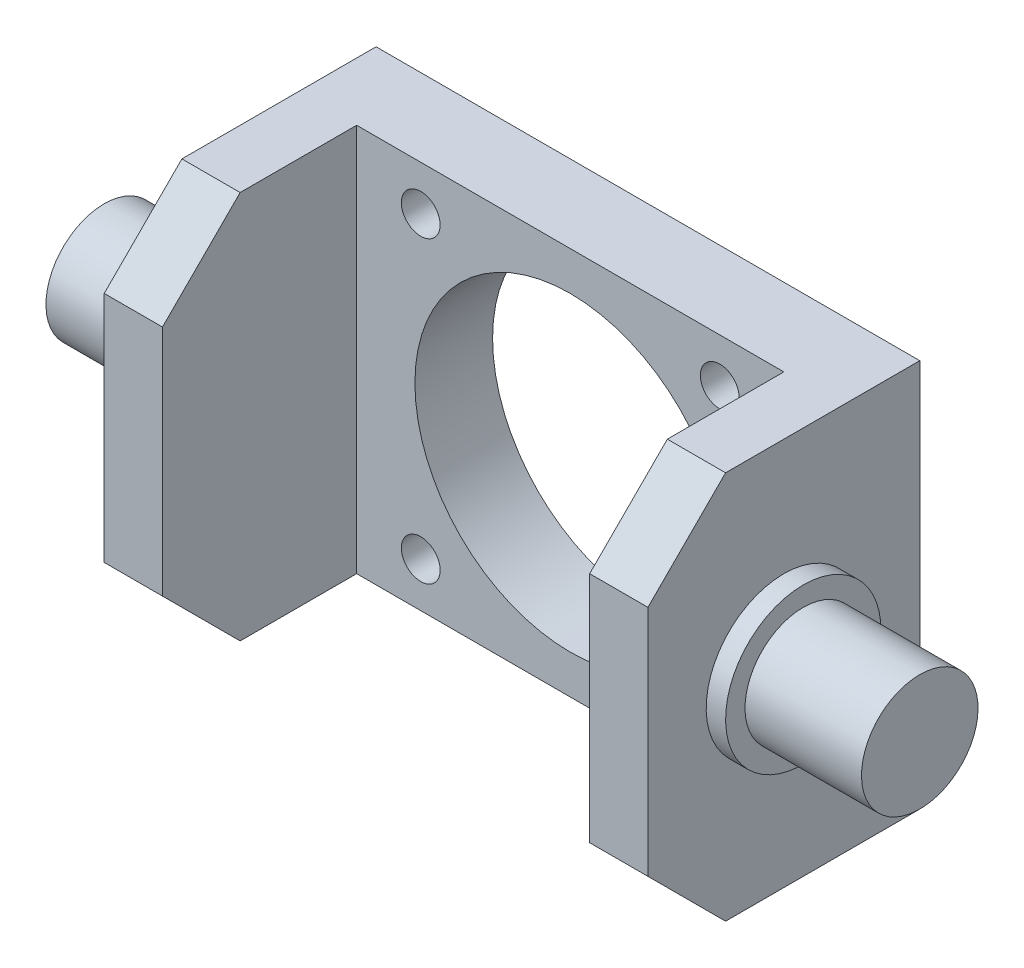
SolidWorks part; units mm, degrees
material "6061 合金"
ref_plane "前视基准面" through (0, 0, 0) normal (0, 0, 1) x (1, 0, 0)
ref_plane "上视基准面" through (0, 0, 0) normal (0, 1, 0) x (1, 0, 0)
ref_plane "右视基准面" through (0, 0, 0) normal (1, 0, 0) x (0, 0, -1)
other "Configuration Table"
sketch "草图1" plane through (0, 0, 0) normal (0, 0, 1) x (1, 0, 0)
  line L1 (-14, 10) -> (14, 10)
  line L2 (-14, 10) -> (-14, -10)
  line L3 (-14, -10) -> (14, -10)
  line L4 (14, 10) -> (14, -10)
  line L5 (-14, 10) -> (14, -10) construction
  line L6 (-14, -10) -> (14, 10) construction
  circle A0 centre (7.7, -7.7) radius 1
  circle A1 centre (0, 0) radius 8
  circle A2 centre (-7.7, -7.7) radius 1
  circle A3 centre (-7.7, 7.7) radius 1
  circle A4 centre (7.7, 7.7) radius 1
  point P0 (0, 0)
  point P10 (-3.4325, 17.5149)
  point P11 (0, 0)
  point P19 (0, 0)
  dimension "D1" = 2
  dimension "D2" = 7.7
  dimension "D3" = 16
  dimension "D4" = 7.7
  dimension "D5" = 28
  dimension "D6" = 20
  dimension "D7" = 4
extrude "凸台-拉伸1" add sketch "草图1" along normal blind 4
sketch "草图2" plane through (0, 0, 4) normal (0, 0, 1) x (1, 0, 0)
  line L0 (-14, -10) -> (14, -10) construction
  line L1 (-14, 10) -> (-11, 10)
  line L2 (-14, 10) -> (-14, -10)
  line L3 (-14, -10) -> (-11, -10)
  line L4 (-11, 10) -> (-11, -10)
  line L6 (14, 10) -> (11, 10)
  line L7 (14, 10) -> (14, -10)
  line L8 (14, -10) -> (11, -10)
  line L9 (11, 10) -> (11, -10)
  dimension "D1" = 3
  dimension "D2" = 3
extrude "凸台-拉伸2" add sketch "草图2" along normal blind 10
sketch "草图3" plane through (14, 0, 0) normal (1, 0, 0) x (0, 0, -1)
  line L0 (0, -10) -> (0, 10) construction
  circle A0 centre (-7, 0) radius 3
  circle A1 centre (-7, 0) radius 7.5
  circle A2 centre (-7, 0) radius 5.25 construction
  circle A3 centre (-7, 0) radius 4
  dimension "D1" = 6
  dimension "D2" = 15
  dimension "D3" = 10.5
  dimension "D4" = 8
  dimension "D5" = 7
extrude "凸台-拉伸3" add sketch "草图3" along normal blind 1 contours A3 A0 | A0
sketch "草图4" plane through (15, 0, 0) normal (1, 0, 0) x (0, 0, -1)
  circle A0 centre (-7, 0) radius 3
  dimension "D1" = 6
extrude "凸台-拉伸4" add sketch "草图4" along normal blind 6
chamfer "倒角1" distance 4 angle 45 4 edges at (-12.5, -10, 14) (-12.5, 10, 14) (12.5, -10, 14) (12.5, 10, 14)
mirror "镜向2" about plane through (0, 0, 0) normal (1, 0, 0) of "凸台-拉伸3", "凸台-拉伸4"
